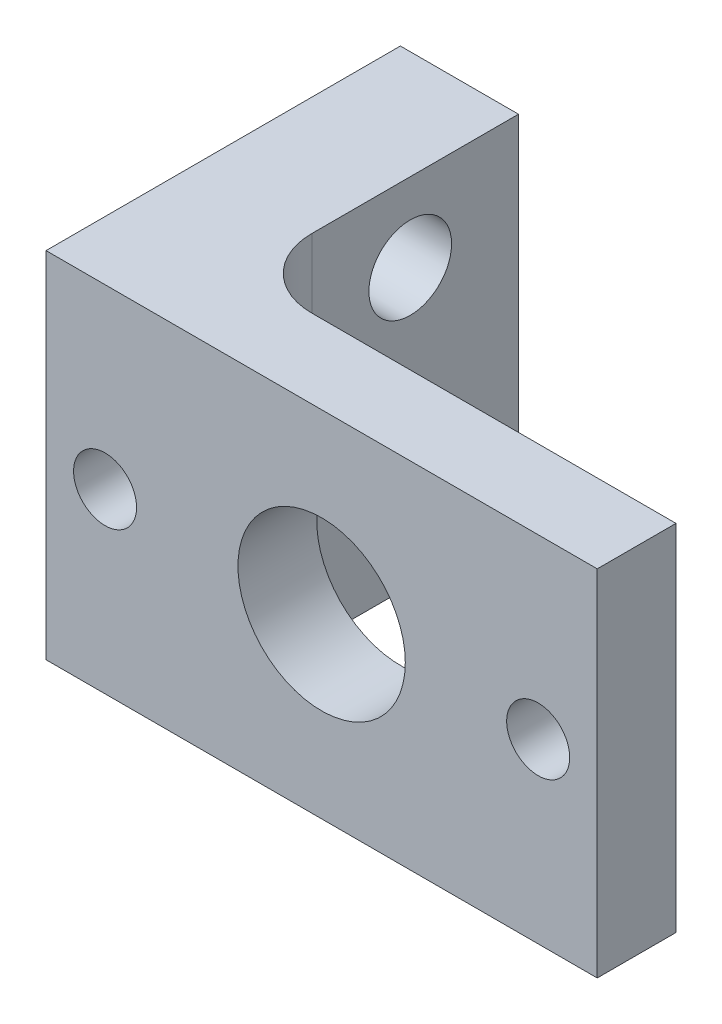
SolidWorks part; units mm, degrees
ref_plane "Front" through (0, 0, 0) normal (0, 0, 1) x (1, 0, 0)
ref_plane "Top" through (0, 0, 0) normal (0, 1, 0) x (1, 0, 0)
ref_plane "Right" through (0, 0, 0) normal (1, 0, 0) x (0, 0, -1)
sketch "Sketch1" plane through (0, 0, 0) normal (0, 1, 0) x (1, 0, 0)
  line L0 (0, 18) -> (0, 0)
  line L1 (0, 0) -> (28, 0)
  line L2 (28, 0) -> (28, 4)
  line L3 (28, 4) -> (6, 4)
  line L4 (6, 4) -> (6, 18)
  line L5 (6, 18) -> (0, 18)
  dimension "D1" = 4
  dimension "D2" = 22
  dimension "D3" = 6
  dimension "D4" = 18
extrude "Boss-Extrude1" add sketch "Sketch1" along normal blind 18
sketch "Sketch4" plane through (0, 0, 0) normal (0, 0, 1) x (1, 0, 0)
  line L0 (0, 18) -> (28, 18) construction
  line L1 (28, 18) -> (28, 0) construction
  line L2 (0, 18) -> (0, 0) construction
  circle A0 centre (25, 9) radius 1.6
  circle A1 centre (3, 9) radius 1.6
  dimension "D1" = 9
  dimension "D2" = 3.2
  dimension "D3" = 3
  dimension "D4" = 3
extrude "Cut-Extrude2" cut sketch "Sketch4" against normal through all
fillet "Fillet1" radius 3.5 1 edges at (6, 9, -4)
sketch "Sketch7" plane through (6, 0, 0) normal (1, 0, 0) x (0, 0, -1)
  line L0 (7.5, 18) -> (18, 18) construction
  line L2 (0, 18) -> (0, 0) construction
  line L3 (26.7565, 9) -> (14.71, 9) construction
  circle A0 centre (12.5, 14) radius 2.1
  circle A1 centre (12.5, 4) radius 2.1
  dimension "D1" = 4.2
  dimension "D2" = 4
  dimension "D3" = 12.5
  dimension "D4" = 9
extrude "Cut-Extrude5" cut sketch "Sketch7" against normal blind 6
sketch "Sketch8" plane through (0, 0, 0) normal (0, 0, 1) x (1, 0, 0)
  line L0 (0, 18) -> (28, 18) construction
  line L1 (0, 18) -> (0, 0) construction
  circle A0 centre (14, 9) radius 4.25
  dimension "D1" = 8.5
  dimension "D2" = 9
  dimension "D3" = 14
extrude "Cut-Extrude6" cut sketch "Sketch8" against normal through all
